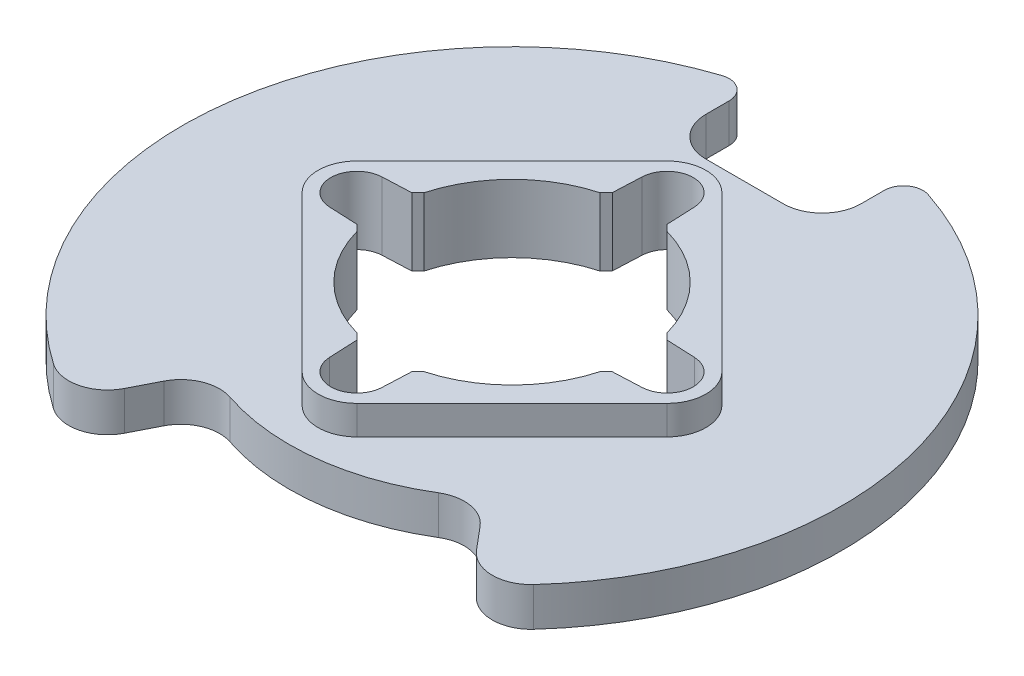
SolidWorks part; units mm, degrees
ref_plane "前视基准面" through (0, 0, 0) normal (0, 0, 1) x (1, 0, 0)
ref_plane "上视基准面" through (0, 0, 0) normal (0, 1, 0) x (1, 0, 0)
ref_plane "右视基准面" through (0, 0, 0) normal (1, 0, 0) x (0, 0, -1)
other "Configuration Table"
sketch "草图1" plane through (0, 0, 0) normal (0, 1, 0) x (1, 0, 0)
  circle A0 centre (0, 8) radius 1.35
  circle A1 centre (0, 0) radius 8 construction
  circle A2 centre (0, 8) radius 2
  circle A3 centre (8, 0) radius 1.35
  circle A4 centre (8, 0) radius 2
  circle A5 centre (0, -8) radius 1.35
  circle A6 centre (0, -8) radius 2
  circle A7 centre (-8, 0) radius 1.35
  circle A8 centre (-8, 0) radius 2
  point P18 (0, 0)
  dimension "D1" = 2.7
  dimension "D2" = 16
  dimension "D3" = 4
  dimension "D4" = 4
extrude "凸台-拉伸1" add sketch "草图1" along normal blind 1.5
sketch "草图2" plane through (0, 0, 0) normal (0, -1, 0) x (1, 0, 0)
  arc A0 (-9.2139, -1.5895) -> (-1.5895, -9.2139) centre (0, 0) ccw
  circle A5 centre (8, 0) radius 1.35 construction
  arc A6 (-7.75, -1.9843) -> (-1.9843, -7.75) centre (0, 0) ccw
  circle A7 centre (0, 8) radius 2 construction
  circle A8 centre (8, 0) radius 2 construction
  circle A9 centre (0, -8) radius 2 construction
  circle A10 centre (-8, 0) radius 2 construction
  arc A11 (1.9843, 7.75) -> (1.5895, 9.2139) centre (0, 8) ccw
  arc A12 (7.75, -1.9843) -> (9.2139, -1.5895) centre (8, 0) ccw
  arc A13 (-1.9843, -7.75) -> (-1.5895, -9.2139) centre (0, -8) ccw
  arc A14 (-9.2139, -1.5895) -> (-7.75, -1.9843) centre (-8, 0) ccw
  arc A15 (-7.75, 1.9843) -> (-9.2139, 1.5895) centre (-8, 0) ccw
  arc A16 (7.75, 1.9843) -> (1.9843, 7.75) centre (0, 0) ccw
  arc A17 (9.2139, 1.5895) -> (1.5895, 9.2139) centre (0, 0) ccw
  arc A18 (9.2139, 1.5895) -> (7.75, 1.9843) centre (8, 0) ccw
  arc A19 (-1.9843, 7.75) -> (-7.75, 1.9843) centre (0, 0) ccw
  arc A20 (-1.5895, 9.2139) -> (-9.2139, 1.5895) centre (0, 0) ccw
  arc A21 (-1.5895, 9.2139) -> (-1.9843, 7.75) centre (0, 8) ccw
  arc A22 (1.9843, -7.75) -> (7.75, -1.9843) centre (0, 0) ccw
  arc A23 (1.5895, -9.2139) -> (9.2139, -1.5895) centre (0, 0) ccw
  arc A24 (1.5895, -9.2139) -> (1.9843, -7.75) centre (0, -8) ccw
extrude "凸台-拉伸2" [suppressed] add sketch "草图2" against normal up to surface (2 mm away)
sketch "草图3" plane through (0, 0, 0) normal (0, -1, 0) x (1, 0, 0)
  line L0 (-1.4142, -6.5858) -> (-6.5858, -1.4142)
  line L1 (-9.4142, -1.4142) -> (-1.4142, -9.4142)
  line L2 (-6.5858, 1.4142) -> (-1.4142, 6.5858)
  line L3 (-1.4142, 9.4142) -> (-9.4142, 1.4142)
  line L4 (1.4142, 6.5858) -> (6.5858, 1.4142)
  line L5 (9.4142, 1.4142) -> (1.4142, 9.4142)
  line L6 (6.5858, -1.4142) -> (1.4142, -6.5858)
  line L7 (1.4142, -9.4142) -> (9.4142, -1.4142)
  circle A0 centre (0, -8) radius 2 construction
  circle A1 centre (-8, 0) radius 2 construction
  circle A2 centre (8, 0) radius 2 construction
  circle A3 centre (0, 8) radius 2 construction
  arc A4 (6.5858, -1.4142) -> (9.4142, -1.4142) centre (8, 0) ccw
  arc A5 (1.4142, 6.5858) -> (1.4142, 9.4142) centre (0, 8) ccw
  arc A6 (-9.4142, -1.4142) -> (-6.5858, -1.4142) centre (-8, 0) ccw
  arc A7 (-6.5858, 1.4142) -> (-9.4142, 1.4142) centre (-8, 0) ccw
  arc A8 (9.4142, 1.4142) -> (6.5858, 1.4142) centre (8, 0) ccw
  arc A9 (-1.4142, 9.4142) -> (-1.4142, 6.5858) centre (0, 8) ccw
  arc A10 (1.4142, 6.5858) -> (1.4142, 9.4142) centre (0, 8) ccw
  arc A11 (6.5858, -1.4142) -> (9.4142, -1.4142) centre (8, 0) ccw
  arc A12 (-1.4142, -6.5858) -> (-1.4142, -9.4142) centre (0, -8) ccw
  arc A13 (-6.5858, 1.4142) -> (-9.4142, 1.4142) centre (-8, 0) ccw
  arc A14 (-9.4142, -1.4142) -> (-6.5858, -1.4142) centre (-8, 0) ccw
  arc A15 (9.4142, 1.4142) -> (6.5858, 1.4142) centre (8, 0) ccw
  arc A16 (-1.4142, 9.4142) -> (-1.4142, 6.5858) centre (0, 8) ccw
  arc A17 (1.4142, -9.4142) -> (1.4142, -6.5858) centre (0, -8) ccw
  point P25 (0, 0)
  circle M4 centre (-8, 0) radius 2
  dimension "D1" = 4
extrude "凸台-拉伸3" add sketch "草图3" against normal up to surface (1.5 mm away) contours A12 L0 L1 M4 | A9 L3 L2 M4 | A8 L5 A5 L4 | A17 L7 A4 L6 up to face at (8, 1.5, 2)
sketch "草图5" plane through (0, 0, 0) normal (0, -1, 0) x (1, 0, 0)
  circle A0 centre (0, 0) radius 6.5
  dimension "D1" = 13
extrude "切除-拉伸1" cut sketch "草图5" against normal through all
sketch "草图4" plane through (0, 0, 0) normal (0, -1, 0) x (1, 0, 0)
  circle A0 centre (0, 0) radius 17
  circle A1 centre (0, 0) radius 6.5
  arc A2 (6.2638, 1.7362) -> (1.7362, 6.2638) centre (0, 0) ccw construction
  dimension "D1" = 34
extrude "凸台-拉伸4" add sketch "草图4" along normal blind 2
sketch "草图8" plane through (0, 0, 0) normal (0, 1, 0) x (1, 0, 0)
  circle A0 centre (8, 0) radius 1.35 construction
  circle A1 centre (0, -8) radius 1.35 construction
  circle A2 centre (-8, 0) radius 1.35 construction
  circle A3 centre (0, 8) radius 1.35 construction
  circle A4 centre (8, 0) radius 1.35
  circle A5 centre (0, -8) radius 1.35
  circle A6 centre (-8, 0) radius 1.35
  circle A7 centre (0, 8) radius 1.35
extrude "切除-拉伸4" cut sketch "草图8" against normal through all and the other way through all
sketch "草图6" plane through (0, 0, 0) normal (0, 1, 0) x (1, 0, 0)
  line L1 (-4, 17) -> (4, 17)
  line L2 (-4, 17) -> (-4, 12)
  line L3 (-4, 12) -> (4, 12)
  line L4 (4, 17) -> (4, 12)
  line L5 (-4, 17) -> (4, 12) construction
  line L6 (-4, 12) -> (4, 17) construction
  circle A1 centre (0, 0) radius 17 construction
  point P0 (0, 14.5)
  dimension "D1" = 8
  dimension "D2" = 5
extrude "切除-拉伸2" cut sketch "草图6" against normal through all
sketch "草图7" plane through (0, 0, 0) normal (0, 1, 0) x (1, 0, 0)
  line L0 (7.3921, -8.8095) -> (10.9274, -13.0228)
  line L1 (-5.2209, -10.2466) -> (-7.7178, -15.1471)
  line L2 (0, 0) -> (0, -24.0866) construction
  arc A0 (-5.2209, -10.2466) -> (7.3921, -8.8095) centre (0, 0) ccw
  arc A1 (-4, 16.5227) -> (4, 16.5227) centre (0, 0) ccw construction
  arc A2 (-7.7178, -15.1471) -> (10.9274, -13.0228) centre (0, 0) ccw
  dimension "D1" = 5.5
  dimension "D2" = 40
  dimension "D3" = 27
extrude "切除-拉伸3" cut sketch "草图7" against normal through all
sketch "草图11" plane through (0, 1.5, 0) normal (0, 1, 0) x (1, 0, 0)
  line L0 (-8.06, 1.3487) -> (-6.5858, 1.4142)
  line L1 (-6.5858, 1.4142) -> (-6.2638, 1.7362)
  line L2 (-8.06, -1.3487) -> (-6.5858, -1.4142)
  line L3 (-6.5858, -1.4142) -> (-6.2638, -1.7362)
  line L4 (1.3487, 8.06) -> (1.4142, 6.5858)
  line L5 (1.4142, 6.5858) -> (1.7362, 6.2638)
  line L6 (-1.3487, 8.06) -> (-1.4142, 6.5858)
  line L7 (-1.4142, 6.5858) -> (-1.7362, 6.2638)
  line L8 (8.06, -1.3487) -> (6.5858, -1.4142)
  line L9 (6.5858, -1.4142) -> (6.2638, -1.7362)
  line L10 (8.06, 1.3487) -> (6.5858, 1.4142)
  line L11 (6.5858, 1.4142) -> (6.2638, 1.7362)
  line L12 (-1.3487, -8.06) -> (-1.4142, -6.5858)
  line L13 (-1.4142, -6.5858) -> (-1.7362, -6.2638)
  line L14 (1.3487, -8.06) -> (1.4142, -6.5858)
  line L15 (1.4142, -6.5858) -> (1.7362, -6.2638)
  circle A0 centre (-8, 0) radius 1.35 construction
  circle A1 centre (0, 8) radius 1.35 construction
  circle A2 centre (8, 0) radius 1.35 construction
  circle A3 centre (0, -8) radius 1.35 construction
  arc A4 (-6.2638, -1.7362) -> (-1.7362, -6.2638) centre (0, 0) ccw construction
  arc A5 (1.7362, -6.2638) -> (6.2638, -1.7362) centre (0, 0) ccw construction
  arc A6 (6.2638, 1.7362) -> (1.7362, 6.2638) centre (0, 0) ccw construction
  arc A7 (-1.7362, 6.2638) -> (-6.2638, 1.7362) centre (0, 0) ccw construction
  arc A8 (1.3487, 8.06) -> (-1.3487, 8.06) centre (0, 8) ccw
  arc A9 (8.06, -1.3487) -> (8.06, 1.3487) centre (8, 0) ccw
  arc A10 (-1.3487, -8.06) -> (1.3487, -8.06) centre (0, -8) ccw
  arc A11 (-6.2638, -1.7362) -> (-1.7362, -6.2638) centre (0, 0) ccw
  arc A12 (1.7362, -6.2638) -> (6.2638, -1.7362) centre (0, 0) ccw
  arc A13 (6.2638, 1.7362) -> (1.7362, 6.2638) centre (0, 0) ccw
  arc A14 (-1.7362, 6.2638) -> (-6.2638, 1.7362) centre (0, 0) ccw
  arc A15 (-8.06, 1.3487) -> (-8.06, -1.3487) centre (-8, 0) ccw
  point P33 (0, 0)
  dimension "D1" = 4
extrude "切除-拉伸5" cut sketch "草图11" against normal through all
fillet "圆角1" radius 2 6 edges at (-4, -1, -12) (4, -1, -12) (10.9274, -1, 13.0228) (7.3921, -1, 8.8095) (-7.7178, -1, 15.1471) (-5.2209, -1, 10.2466)
fillet "圆角2" radius 1 2 edges at (4, -1, -16.5227) (-4, -1, -16.5227)
